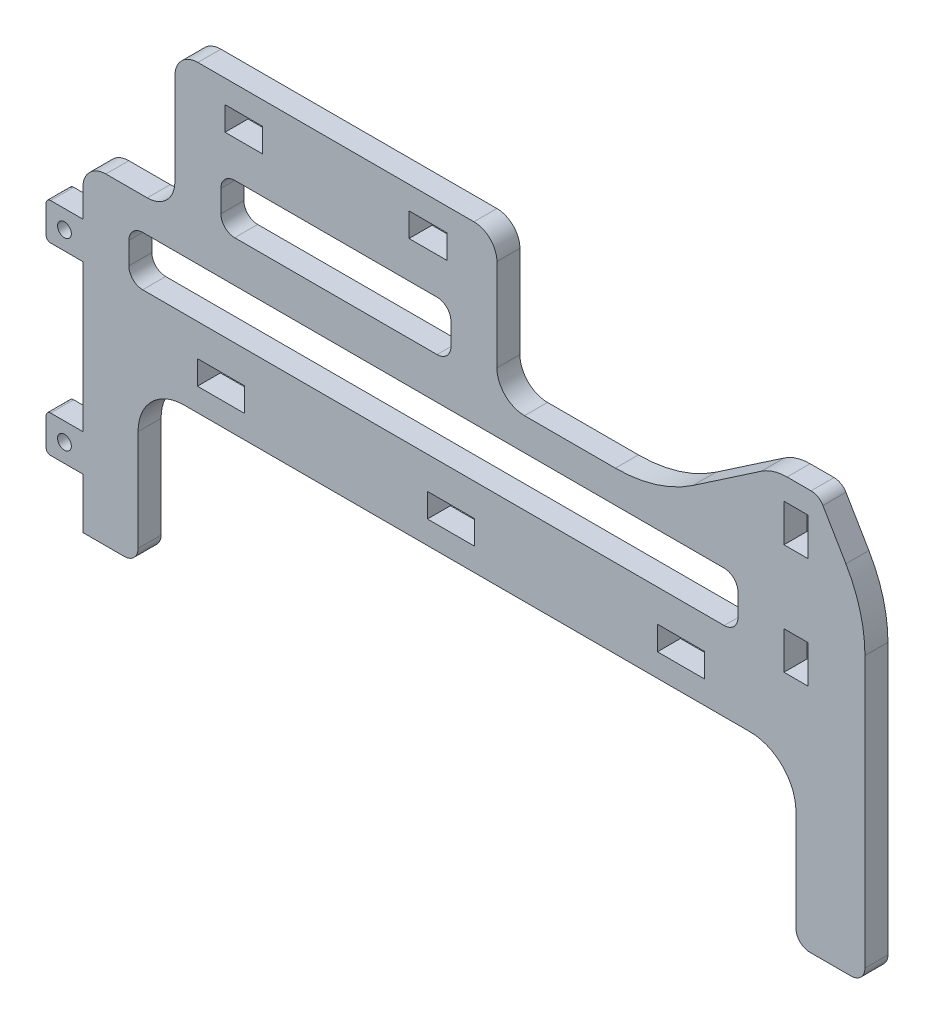
SolidWorks part; units mm, degrees
ref_plane "Alzado" through (0, 0, 0) normal (0, 0, 1) x (1, 0, 0)
ref_plane "Planta" through (0, 0, 0) normal (0, 1, 0) x (1, 0, 0)
ref_plane "Vista lateral" through (0, 0, 0) normal (1, 0, 0) x (0, 0, -1)
sketch "Croquis1" plane through (0, 0, 0) normal (0, 0, 1) x (1, 0, 0)
  line L0 (0, 0) -> (0, 70)
  line L1 (0, 70) -> (125, 70)
  line L2 (125, 70) -> (150, 87)
  line L3 (150, 87) -> (160, 87)
  line L4 (160, 87) -> (170, 70)
  line L5 (170, 70) -> (170, 0)
  line L6 (170, 0) -> (0, 0)
  dimension "D1" = 17
  dimension "D2" = 70
  dimension "D3" = 125
  dimension "D4" = 10
  dimension "D5" = 10
  dimension "D6" = 25
extrude "Saliente-Extruir1" add sketch "Croquis1" along normal blind 5
sketch "Croquis2" plane through (0, 0, 5) normal (0, 0, 1) x (1, 0, 0)
  line L0 (0, 0) -> (170, 0) construction
  line L1 (12, 0) -> (155, 0)
  line L2 (12, 0) -> (12, 35)
  line L3 (12, 35) -> (155, 35)
  line L4 (155, 0) -> (155, 35)
  line L5 (170, 0) -> (170, 70) construction
  line L6 (0, 70) -> (0, 0) construction
  dimension "D1" = 15
  dimension "D2" = 35
  dimension "D3" = 12
extrude "Cortar-Extruir1" cut sketch "Croquis2" against normal blind 5
fillet "Redondeo1" radius 10 2 edges at (155, 35, 2.5) (12, 35, 2.5)
sketch "Croquis3" plane through (0, 0, 0) normal (-1, 0, 0) x (0, 0, 1)
  line L0 (5, 70) -> (5, 0) construction
  line L1 (5, 11) -> (0, 11)
  line L2 (5, 11) -> (5, 19)
  line L3 (5, 19) -> (0, 19)
  line L4 (0, 11) -> (0, 19)
  line L5 (0, 70) -> (0, 0) construction
  line L6 (5, 0) -> (0, 0) construction
  line L7 (5, 59) -> (0, 59)
  line L8 (5, 59) -> (5, 51)
  line L9 (5, 51) -> (0, 51)
  line L10 (0, 59) -> (0, 51)
  point P12 (5, 15)
  point P16 (5, 55)
  dimension "D1" = 8
  dimension "D2" = 8
  dimension "D3" = 15
  dimension "D4" = 55
extrude "Saliente-Extruir2" add sketch "Croquis3" along normal blind 8
fillet "Redondeo2" radius 30 2 edges at (125, 70, 2.5) (170, 70, 2.5)
fillet "Redondeo3" radius 3 3 edges at (155, 0, 2.5) (12, 0, 2.5) (170, 0, 2.5)
sketch "Croquis4" plane through (0, 0, 5) normal (0, 0, 1) x (1, 0, 0)
  line L0 (160, 87) -> (150, 87) construction
  line L1 (152.4, 82.1) -> (157.6, 82.1)
  line L2 (152.4, 82.1) -> (152.4, 73.9)
  line L3 (152.4, 73.9) -> (157.6, 73.9)
  line L4 (157.6, 82.1) -> (157.6, 73.9)
  line L5 (152.4, 58.1) -> (157.6, 58.1)
  line L6 (152.4, 58.1) -> (152.4, 49.9)
  line L7 (152.4, 49.9) -> (157.6, 49.9)
  line L8 (157.6, 58.1) -> (157.6, 49.9)
  line L9 (0, 70) -> (0, 59) construction
  point P9 (152.4, 78)
  point P10 (152.4, 54)
  point P13 (155, 82.1)
  dimension "D1" = 5.2
  dimension "D2" = 8.2
  dimension "D3" = 5.2
  dimension "D4" = 8.2
  dimension "D5" = 24
  dimension "D6" = 4.9
  dimension "D7" = 155
extrude "Cortar-Extruir2" cut sketch "Croquis4" against normal through all
fillet "Redondeo4" radius 3 1 edges at (160, 87, 2.5)
fillet "Redondeo5" radius 10 1 edges at (150, 87, 2.5)
fillet "Redondeo6" radius 1 4 edges at (-8, 11, 2.5) (-8, 19, 2.5) (-8, 51, 2.5) (-8, 59, 2.5)
sketch "Croquis5" plane through (0, 0, 5) normal (0, 0, 1) x (1, 0, 0)
  line L0 (-8, 52) -> (-8, 58) construction
  line L1 (-8, 12) -> (-8, 18) construction
  circle A0 centre (-4, 55) radius 1.5
  circle A1 centre (-4, 15) radius 1.5
  point P7 (-8, 55)
  point P12 (-8, 15)
  dimension "D1" = 3
  dimension "D2" = 4
extrude "Cortar-Extruir3" cut sketch "Croquis5" against normal blind 5
sketch "Croquis6" plane through (0, 0, 5) normal (0, 0, 1) x (1, 0, 0)
  line L0 (74.9, 45.2) -> (85.1, 45.2)
  line L1 (24.9, 45.2) -> (35.1, 45.2)
  line L2 (24.9, 45.2) -> (24.9, 40)
  line L3 (24.9, 40) -> (35.1, 40)
  line L4 (35.1, 45.2) -> (35.1, 40)
  line L5 (74.9, 45.2) -> (74.9, 40)
  line L6 (74.9, 40) -> (85.1, 40)
  line L7 (85.1, 45.2) -> (85.1, 40)
  line L8 (124.9, 45.2) -> (135.1, 45.2)
  line L9 (124.9, 45.2) -> (124.9, 40)
  line L10 (124.9, 40) -> (135.1, 40)
  line L11 (135.1, 45.2) -> (135.1, 40)
  line L12 (145, 35) -> (22, 35) construction
  line L13 (0, 51) -> (0, 19) construction
  point P14 (30, 40)
  point P15 (80, 40)
  point P16 (130, 40)
  dimension "D1" = 5.2
  dimension "D2" = 10.2
  dimension "D3" = 5.2
  dimension "D4" = 10.2
  dimension "D5" = 5.2
  dimension "D6" = 10.2
  dimension "D7" = 50
  dimension "D8" = 50
  dimension "D9" = 5
  dimension "D10" = 30
extrude "Cortar-Extruir4" cut sketch "Croquis6" against normal blind 5
sketch "Croquis7" plane through (0, 0, 5) normal (0, 0, 1) x (1, 0, 0)
  line L0 (0, 70) -> (0, 59) construction
  line L1 (10, 63) -> (142.4, 63)
  line L2 (10, 63) -> (10, 52.2)
  line L3 (10, 52.2) -> (142.4, 52.2)
  line L4 (142.4, 63) -> (142.4, 52.2)
  line L5 (115.7663, 70) -> (0, 70) construction
  line L6 (35.1, 45.2) -> (24.9, 45.2) construction
  line L7 (152.4, 58.1) -> (152.4, 49.9) construction
  dimension "D1" = 10
  dimension "D2" = 7
  dimension "D3" = 7
  dimension "D4" = 10
extrude "Cortar-Extruir5" cut sketch "Croquis7" against normal blind 5
fillet "Redondeo8" radius 3 4 edges at (142.4, 52.2, 2.5) (142.4, 63, 2.5) (10, 52.2, 2.5) (10, 63, 2.5)
sketch "Croquis8" plane through (0, 0, 5) normal (0, 0, 1) x (1, 0, 0)
  line L0 (115.7663, 70) -> (0, 70) construction
  line L1 (20, 70) -> (90, 70)
  line L2 (20, 70) -> (20, 101)
  line L3 (20, 101) -> (90, 101)
  line L4 (90, 70) -> (90, 101)
  line L5 (0, 70) -> (0, 59) construction
  dimension "D1" = 31
  dimension "D2" = 70
  dimension "D3" = 20
extrude "Saliente-Extruir3" add sketch "Croquis8" against normal blind 5
sketch "Croquis9" plane through (0, 0, 5) normal (0, 0, 1) x (1, 0, 0)
  line L0 (20, 101) -> (20, 70) construction
  line L1 (30.9, 96) -> (39.1, 96)
  line L2 (30.9, 96) -> (30.9, 90.8)
  line L3 (30.9, 90.8) -> (39.1, 90.8)
  line L4 (39.1, 96) -> (39.1, 90.8)
  line L5 (70.9, 96) -> (79.1, 96)
  line L6 (70.9, 96) -> (70.9, 90.8)
  line L7 (70.9, 90.8) -> (79.1, 90.8)
  line L8 (79.1, 96) -> (79.1, 90.8)
  line L9 (90, 70) -> (90, 101) construction
  line L10 (90, 101) -> (20, 101) construction
  point P8 (35, 96)
  point P11 (75, 96)
  dimension "D1" = 8.2
  dimension "D2" = 5.2
  dimension "D3" = 8.2
  dimension "D4" = 5.2
  dimension "D5" = 15
  dimension "D6" = 15
  dimension "D7" = 5
extrude "Cortar-Extruir6" cut sketch "Croquis9" against normal blind 5
sketch "Croquis10" plane through (0, 0, 5) normal (0, 0, 1) x (1, 0, 0)
  line L0 (20, 101) -> (20, 70) construction
  line L1 (30, 82.8) -> (80, 82.8)
  line L2 (30, 82.8) -> (30, 72)
  line L3 (30, 72) -> (80, 72)
  line L4 (80, 82.8) -> (80, 72)
  line L5 (30.9, 90.8) -> (39.1, 90.8) construction
  line L6 (139.4, 63) -> (13, 63) construction
  line L7 (90, 70) -> (90, 101) construction
  dimension "D1" = 10
  dimension "D2" = 8
  dimension "D3" = 9
  dimension "D4" = 10
extrude "Cortar-Extruir7" cut sketch "Croquis10" against normal blind 5
fillet "Redondeo9" radius 3 4 edges at (30, 72, 2.5) (80, 72, 2.5) (80, 82.8, 2.5) (30, 82.8, 2.5)
fillet "Redondeo10" radius 6 2 edges at (90, 70, 2.5) (20, 70, 2.5)
fillet "Redondeo11" radius 5 2 edges at (90, 101, 2.5) (20, 101, 2.5)
fillet "Redondeo12" radius 5 1 edges at (0, 70, 2.5)
